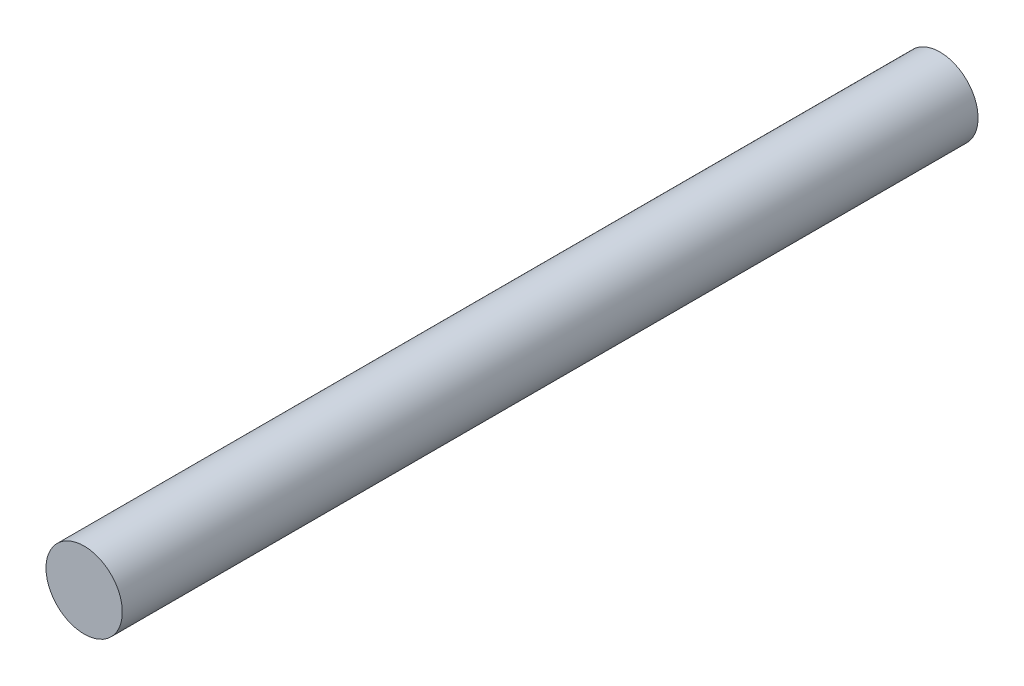
SolidWorks part; units mm, degrees
ref_plane "Front Plane" through (0, 0, 0) normal (0, 0, 1) x (1, 0, 0)
ref_plane "Top Plane" through (0, 0, 0) normal (0, 1, 0) x (1, 0, 0)
ref_plane "Right Plane" through (0, 0, 0) normal (1, 0, 0) x (0, 0, -1)
sketch "Sketch1" plane through (0, 0, 0) normal (0, 0, 1) x (1, 0, 0)
  circle A0 centre (0, 0) radius 2.5908
  dimension "D1" = 5.1816
extrude "Boss-Extrude1" add sketch "Sketch1" along normal blind 58.1
